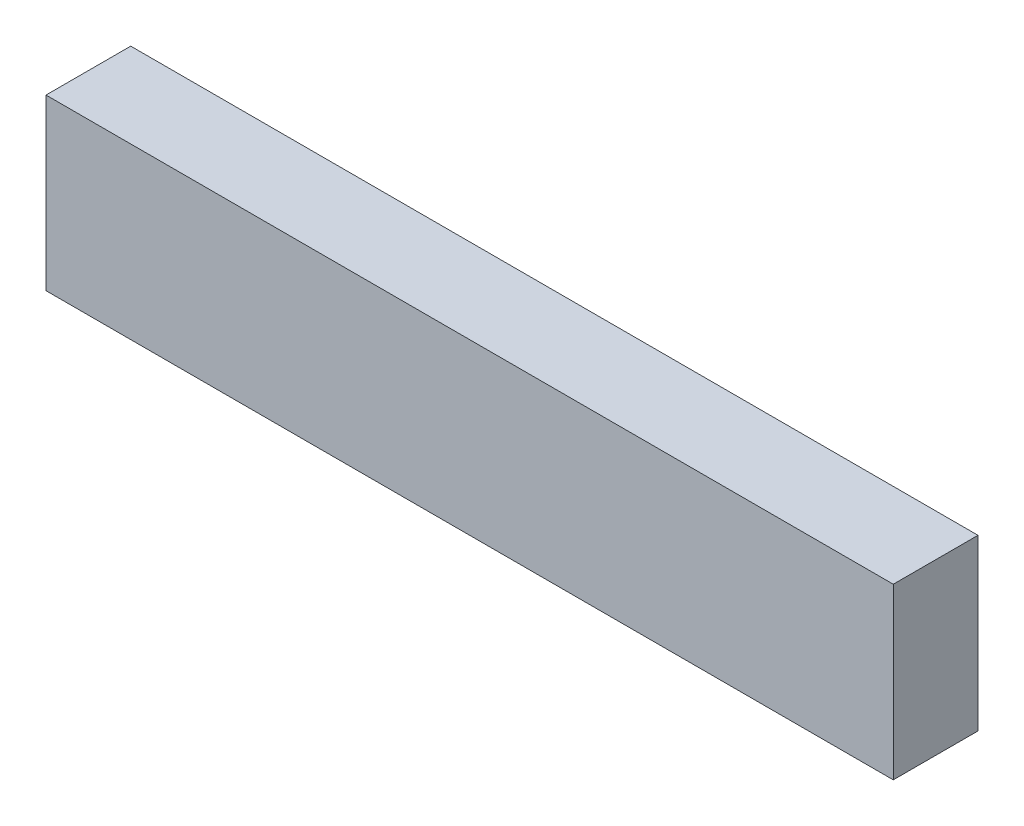
SolidWorks part; units mm, degrees
ref_plane "Front Plane" through (0, 0, 0) normal (0, 0, 1) x (1, 0, 0)
ref_plane "Top Plane" through (0, 0, 0) normal (0, 1, 0) x (1, 0, 0)
ref_plane "Right Plane" through (0, 0, 0) normal (1, 0, 0) x (0, 0, -1)
other "Configuration Table"
sketch "Sketch1" plane through (0, 0, 0) normal (0, 0, 1) x (1, 0, 0)
  line L1 (0, 0) -> (254, 0)
  line L2 (0, 0) -> (0, 50.8)
  line L3 (0, 50.8) -> (254, 50.8)
  line L4 (254, 0) -> (254, 50.8)
  dimension "D1" = 50.8
  dimension "D2" = 254
extrude "Extrude1" add sketch "Sketch1" along normal blind 25.4
